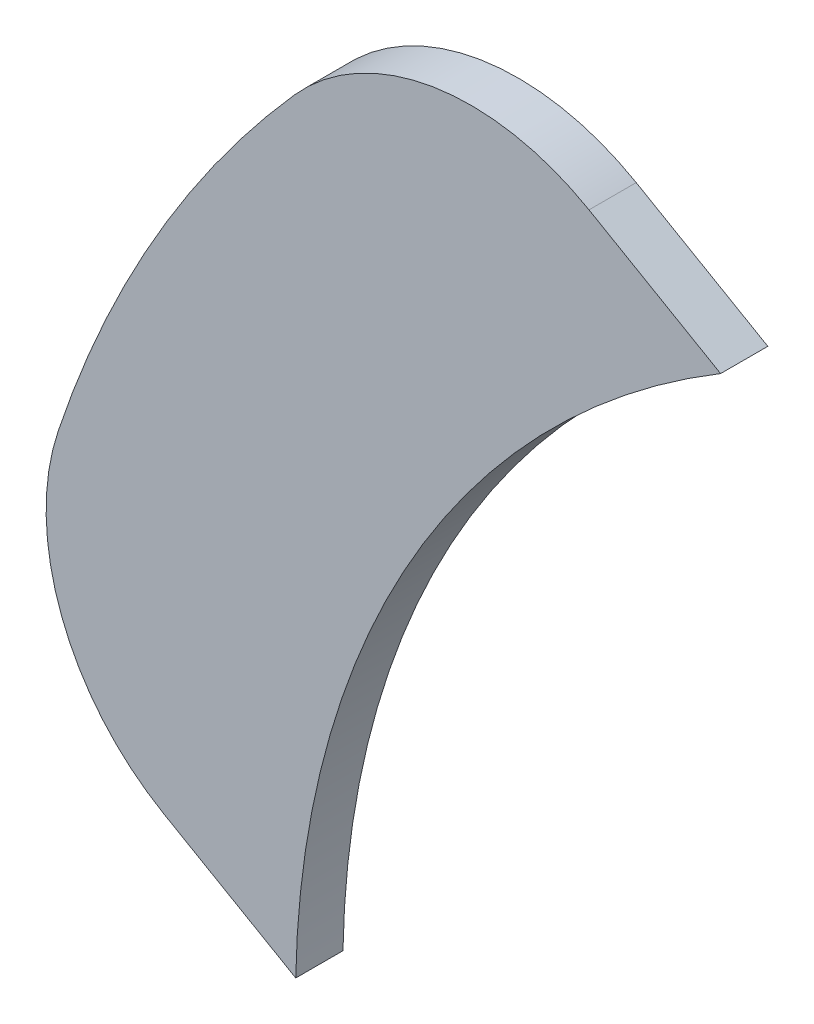
SolidWorks part; units mm, degrees
ref_plane "Front Plane" through (0, 0, 0) normal (0, 0, 1) x (1, 0, 0)
ref_plane "Top Plane" through (0, 0, 0) normal (0, 1, 0) x (1, 0, 0)
ref_plane "Right Plane" through (0, 0, 0) normal (1, 0, 0) x (0, 0, -1)
sketch "Sketch1" plane through (0, 0, 0) normal (0, 0, 1) x (1, 0, 0)
  line L0 (-42.7201, 3.8799) -> (-37.1441, 0.6606) construction
  line L1 (-42.7201, 3.8799) -> (-37.1441, 0.6606)
  line L2 (0, 0) -> (-43.0848, 24.875) construction
  line L3 (-24.7201, 35.0568) -> (-19.1441, 31.8375)
  arc A0 (-19.1441, 31.8375) -> (-37.1441, 0.6606) centre (0, 0) ccw
  arc A1 (-47.2095, 15.6949) -> (-42.7201, 3.8799) centre (-37.7201, 12.5401) ccw construction
  arc A2 (-37.1969, 33.0372) -> (-47.2095, 15.6949) centre (0, 0) ccw construction
  arc A3 (-47.2095, 15.6949) -> (-42.7201, 3.8799) centre (-37.7201, 12.5401) ccw
  arc A4 (-37.1969, 33.0372) -> (-47.2095, 15.6949) centre (0, 0) ccw
  arc A5 (-37.1969, 33.0372) -> (-24.7201, 35.0568) centre (-29.7201, 26.3965) cw
extrude "Boss-Extrude1" add sketch "Sketch1" along normal blind 2
